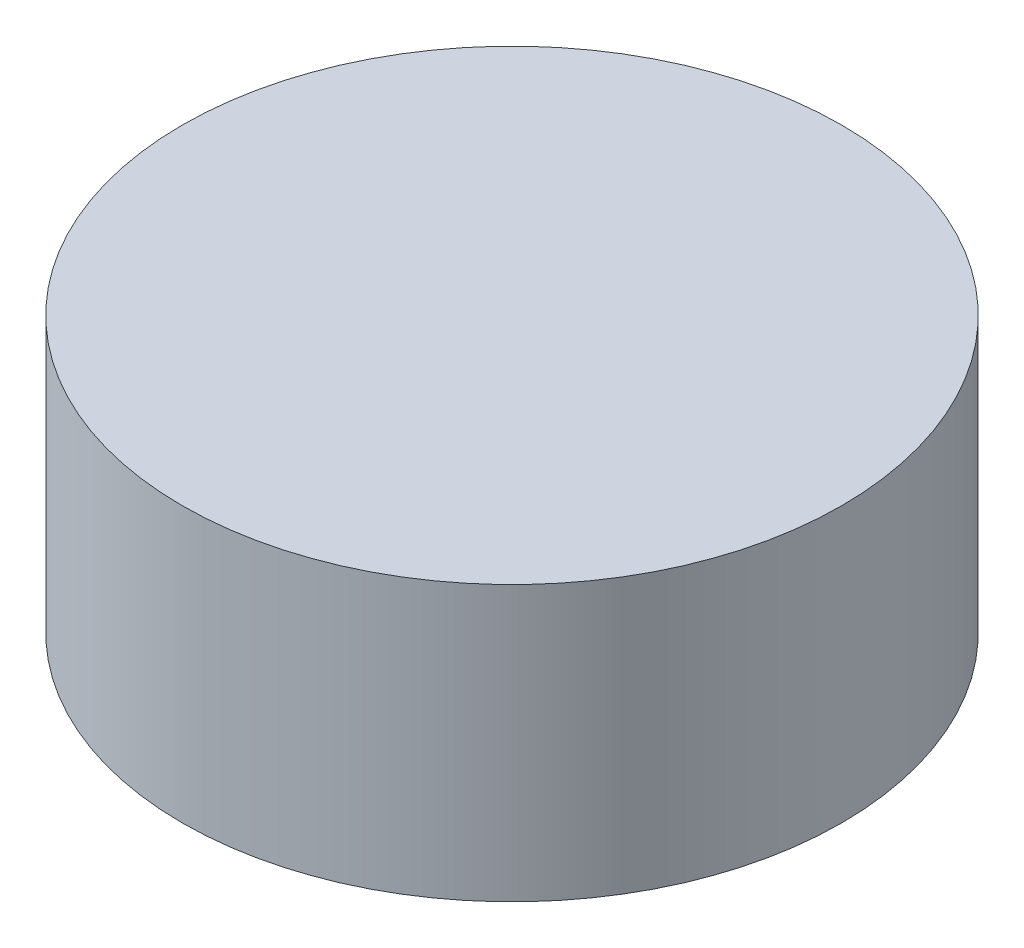
SolidWorks part; units mm, degrees
ref_plane "Front Plane" through (0, 0, 0) normal (0, 0, 1) x (1, 0, 0)
ref_plane "Top Plane" through (0, 0, 0) normal (0, 1, 0) x (1, 0, 0)
ref_plane "Right Plane" through (0, 0, 0) normal (1, 0, 0) x (0, 0, -1)
sketch "Sketch1" plane through (0, 0, 0) normal (0, 1, 0) x (1, 0, 0)
  circle A0 centre (0, 0) radius 3
  dimension "D1" = 6
extrude "Boss-Extrude1" add sketch "Sketch1" along normal blind 2.5
equation "\"a\"= 1"
equation "\"b\"= 1"
equation "\"c\"= 1"
equation "\"d\"= 1"
equation "\"e\"= 1"
equation "\"x\"= 1"
equation "\"y\"= 1"
equation "\"z\"= 1"
